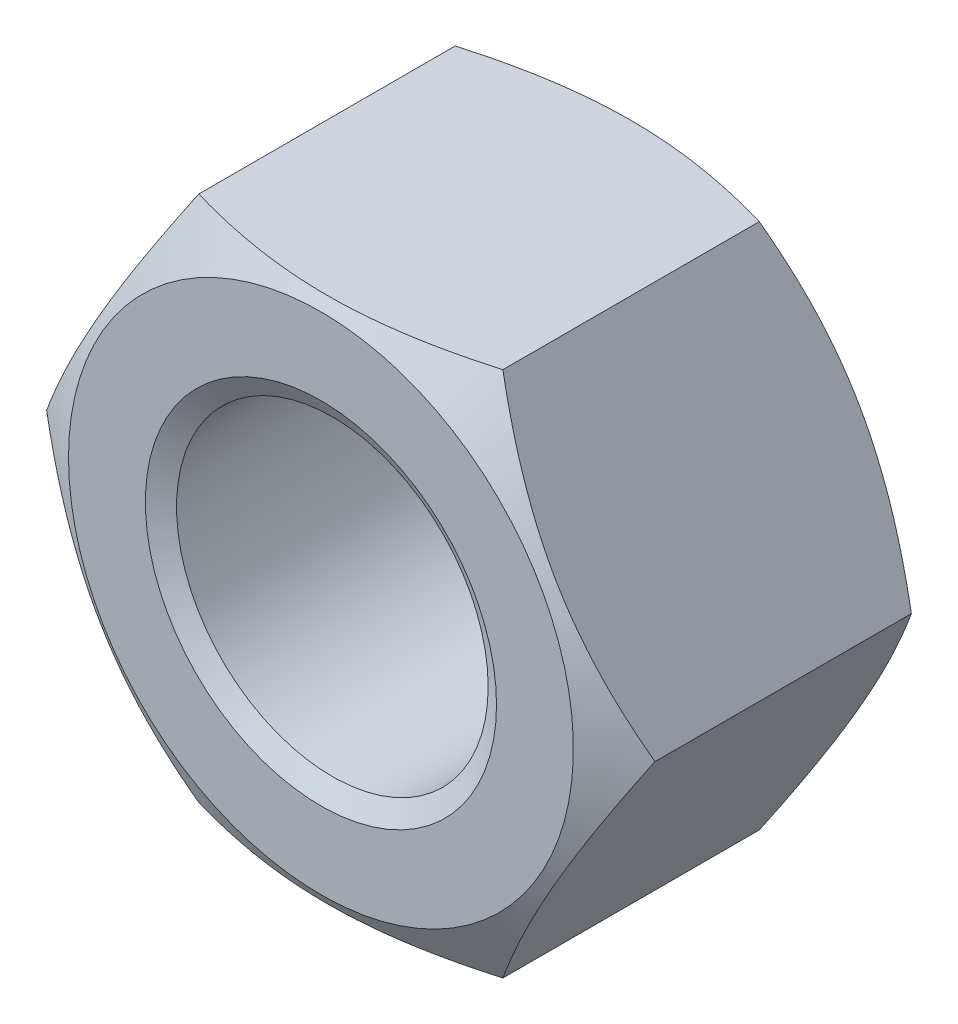
SolidWorks part; units mm, degrees
ref_plane "Front" through (0, 0, 0) normal (0, 0, 1) x (1, 0, 0)
ref_plane "Top" through (0, 0, 0) normal (0, 1, 0) x (1, 0, 0)
ref_plane "Right" through (0, 0, 0) normal (1, 0, 0) x (0, 0, -1)
other "Configuration Table"
sketch "Sketch1" plane through (0, 0, 0) normal (0, 0, 1) x (1, 0, 0)
  line L1 (5.1962, -9) -> (10.3923, 0)
  line L2 (10.3923, 0) -> (5.1962, 9)
  line L3 (5.1962, 9) -> (-5.1962, 9)
  line L4 (-5.1962, 9) -> (-10.3923, 0)
  line L5 (-10.3923, 0) -> (-5.1962, -9)
  line L6 (-5.1962, -9) -> (5.1962, -9)
  circle A0 centre (0, 0) radius 9 construction
  circle A1 centre (0, 0) radius 5.3235
  dimension "D" = 10.647
  dimension "s" = 18
extrude "BaseNut" add sketch "Sketch1" against normal blind 10.8
cosmetic thread "ThreadCosmetic1" [suppressed] parameters "D"=12
sketch "Sketch2" plane through (0, 0, 0) normal (0, 1, 0) x (1, 0, 0)
  line L0 (-10.3923, 10.8) -> (-8.625, 10.8)
  line L2 (-8.625, 10.8) -> (-10.3923, 9.7796)
  line L3 (-10.3923, 9.7796) -> (-10.3923, 10.8)
  line L4 (0, 9.8171) -> (0, -9.8171) construction
  line L6 (-9.7712, 5.4) -> (9.8853, 5.4) construction
  line L7 (-10.3923, 1.0204) -> (-10.3923, 0)
  line L8 (-8.625, 0) -> (-10.3923, 1.0204)
  line L9 (-10.3923, 0) -> (-8.625, 0)
  dimension "dw" = 17.25
  dimension "D1" = 30
  dimension "D2" = 5.4
revolve "Double-Chamfer" cut sketch "Sketch2" angle 360 about L4
chamfer "EndChamfer" distance 0.675 angle 30 2 edges at (5.3235, 0, -10.8) (5.3235, 0, 0)
sketch "Sketch3" plane through (0, 0, 0) normal (0, 1, 0) x (1, 0, 0)
  line L0 (-5.9094, 10.125) -> (-5.3235, 9.7868)
  line L1 (-5.3235, 9.7868) -> (-4.647, 9.7868)
  line L2 (-4.647, 9.7868) -> (-4.647, 10.4633)
  line L3 (-4.647, 10.4633) -> (-5.3235, 10.4633)
  line L4 (-5.3235, 10.4633) -> (-5.9094, 10.125)
  line L5 (0, 5.5171) -> (0, 12.3415) construction
  dimension "D1" = 0.6765
  dimension "D2" = 10.647
revolve "Cut-Revolve10" [suppressed] cut sketch "Sketch3" angle 360 about L5
pattern_linear "LPattern10" [suppressed] count 12 spacing 0.8118 along (0, 0, -1)
equation "\"dw@Sketch2\" = \"s@Sketch1\"-0.75"
equation "\"D1@EndChamfer\" = \"m@BaseNut\" / 16"
equation "\"D2@Sketch2\" = \"m@BaseNut\" / 2"
equation "\"D2@Sketch3\"=\"D@Sketch1\""
equation "\"D1@Sketch3\" =  ( \"D@ThreadCosmetic1\" - \"D@Sketch1\" )  / 2"
equation "\"D3@LPattern10\"=\"D1@Sketch3\" * 1.2"
equation "\"D1@LPattern10\" = \"m@BaseNut\" / \"D3@LPattern10\"-1"
